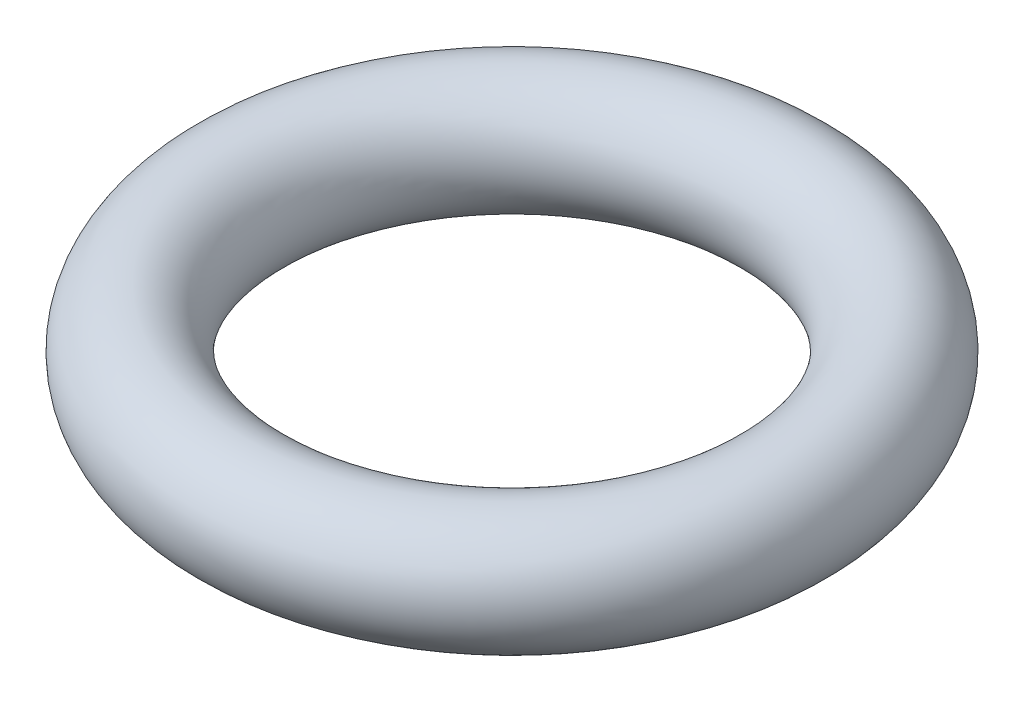
SolidWorks part; units mm, degrees
ref_plane "Alzado" through (0, 0, 0) normal (0, 0, 1) x (1, 0, 0)
ref_plane "Planta" through (0, 0, 0) normal (0, 1, 0) x (1, 0, 0)
ref_plane "Vista lateral" through (0, 0, 0) normal (1, 0, 0) x (0, 0, -1)
sketch "Croquis1" plane through (0, 0, 0) normal (0, 1, 0) x (1, 0, 0)
  line L0 (0, 0) -> (3.65, 0) construction
  circle A0 centre (0, 0) radius 3.65
  dimension "D1" = 7.3
sketch "Croquis2" plane through (0, 0, 0) normal (1, 0, 0) x (0, 0, -1)
  circle A0 centre (3.65, 0) radius 0.8
  point P2 (0, 0)
  dimension "D1" = 3.65
  dimension "D2" = 1.6
sweep "Barrer1" add profiles "Croquis2" path "Croquis1"
